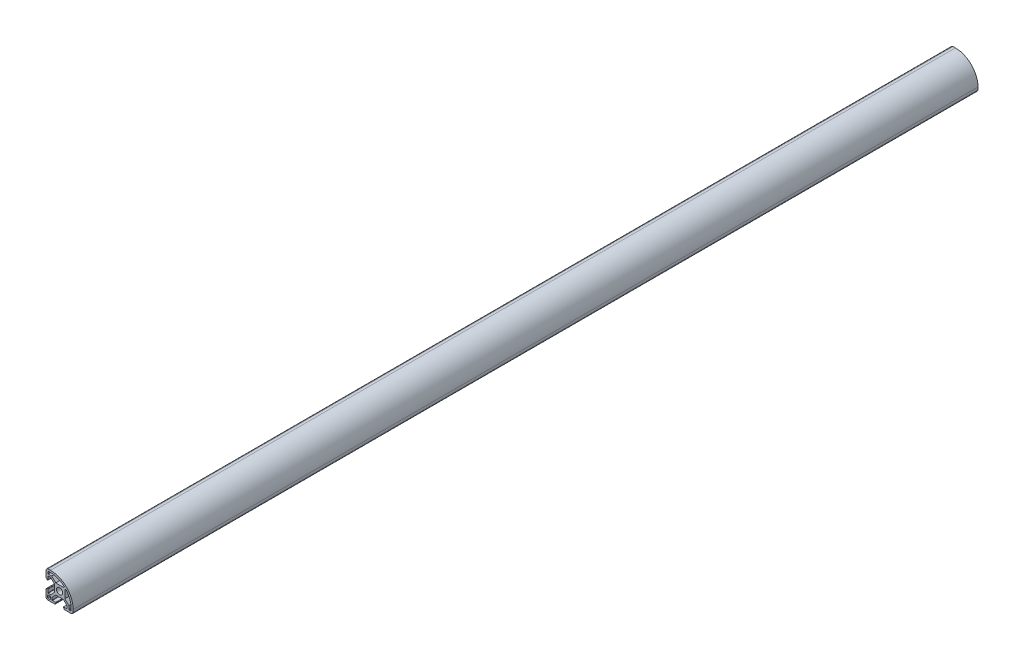
SolidWorks part; units mm, degrees
ref_plane "前视基准面" through (0, 0, 0) normal (0, 0, 1) x (1, 0, 0)
ref_plane "上视基准面" through (0, 0, 0) normal (0, 1, 0) x (1, 0, 0)
ref_plane "右视基准面" through (0, 0, 0) normal (1, 0, 0) x (0, 0, -1)
sketch "草图1" plane through (0, 0, 0) normal (0, 0, 1) x (1, 0, 0)
  line L0 (-29.9574, -7.0303) -> (-29.9574, -14.4303)
  line L1 (-9.632, 4.9507) -> (-10.7131, 3.8697)
  line L2 (-10.7131, 3.8697) -> (-19.2018, 3.8697)
  line L3 (-19.2018, 3.8697) -> (-23.6518, 8.3197)
  line L4 (-24.9574, 13.0697) -> (-27.4574, 13.0697)
  line L5 (-29.9574, 10.5697) -> (-29.9574, 3.1697)
  line L6 (-29.9574, 3.1697) -> (-29.1574, 3.1697)
  line L7 (-28.9574, 2.9697) -> (-28.9574, 2.1697)
  line L8 (-28.9574, 2.1697) -> (-28.0574, 2.1697)
  line L9 (-27.7574, 2.4697) -> (-27.7574, 6.0197)
  line L10 (-27.4574, 6.3197) -> (-24.7631, 6.3197)
  line L11 (-24.7631, 6.3197) -> (-20.7574, 2.314)
  line L12 (-20.7574, 2.314) -> (-20.7574, -6.1747)
  line L13 (-20.7574, -6.1747) -> (-24.7631, -10.1803)
  line L14 (-24.7631, -10.1803) -> (-27.4574, -10.1803)
  line L15 (-27.7574, -9.8803) -> (-27.7574, -6.3303)
  line L16 (-28.0574, -6.0303) -> (-28.9574, -6.0303)
  line L17 (-28.9574, -6.0303) -> (-28.9574, -6.8303)
  line L18 (-29.1574, -7.0303) -> (-29.9574, -7.0303)
  line L20 (-27.4574, -16.9303) -> (-20.0574, -16.9303)
  line L21 (-20.0574, -16.9303) -> (-20.0574, -16.1303)
  line L22 (-19.8574, -15.9303) -> (-19.0574, -15.9303)
  line L23 (-19.0574, -15.9303) -> (-19.0574, -15.0303)
  line L24 (-19.3574, -14.7303) -> (-22.9074, -14.7303)
  line L25 (-23.2074, -14.4303) -> (-23.2074, -11.736)
  line L26 (-23.2074, -11.736) -> (-19.2018, -7.7303)
  line L27 (-19.2018, -7.7303) -> (-10.7131, -7.7303)
  line L28 (-10.7131, -7.7303) -> (-6.7074, -11.736)
  line L29 (-6.7074, -11.736) -> (-6.7074, -14.4303)
  line L30 (-7.0074, -14.7303) -> (-10.5574, -14.7303)
  line L31 (-10.8574, -15.0303) -> (-10.8574, -15.9303)
  line L32 (-10.8574, -15.9303) -> (-10.0574, -15.9303)
  line L33 (-9.8574, -16.1303) -> (-9.8574, -16.9303)
  line L34 (-9.8574, -16.9303) -> (-2.4574, -16.9303)
  line L35 (0.0426, -14.4303) -> (0.0426, -11.9303)
  line L36 (-24.9574, 10.8697) -> (-27.4574, 10.8697)
  line L37 (-27.7574, 10.5697) -> (-27.7574, 8.6197)
  line L38 (-27.4574, 8.3197) -> (-23.6518, 8.3197)
  line L39 (-27.9324, -15.2053) -> (-25.2324, -15.2053)
  line L40 (-24.9324, -14.9053) -> (-24.9324, -12.2053)
  line L41 (-25.2324, -11.9053) -> (-27.9324, -11.9053)
  line L42 (-28.2324, -12.2053) -> (-28.2324, -14.9053)
  line L44 (-8.0764, 3.3951) -> (-9.1574, 2.314)
  line L45 (-9.1574, 2.314) -> (-9.1574, -6.1747)
  line L46 (-9.1574, -6.1747) -> (-4.7074, -10.6247)
  line L47 (-2.1574, -11.9303) -> (-2.1574, -14.4303)
  line L48 (-2.4574, -14.7303) -> (-4.4074, -14.7303)
  line L49 (-4.7074, -14.4303) -> (-4.7074, -10.6247)
  circle A0 centre (-14.9574, -1.9303) radius 3.4
  arc A1 (-27.4574, 13.0697) -> (-29.9574, 10.5697) centre (-27.4574, 10.5697) ccw
  arc A2 (-28.9574, 2.9697) -> (-29.1574, 3.1697) centre (-29.1574, 2.9697) ccw
  arc A3 (-28.0574, 2.1697) -> (-27.7574, 2.4697) centre (-28.0574, 2.4697) ccw
  arc A4 (-27.4574, 6.3197) -> (-27.7574, 6.0197) centre (-27.4574, 6.0197) ccw
  arc A5 (-27.7574, -9.8803) -> (-27.4574, -10.1803) centre (-27.4574, -9.8803) ccw
  arc A6 (-27.7574, -6.3303) -> (-28.0574, -6.0303) centre (-28.0574, -6.3303) ccw
  arc A7 (-29.1574, -7.0303) -> (-28.9574, -6.8303) centre (-29.1574, -6.8303) ccw
  arc A8 (-29.9574, -14.4303) -> (-27.4574, -16.9303) centre (-27.4574, -14.4303) ccw
  arc A9 (-19.8574, -15.9303) -> (-20.0574, -16.1303) centre (-19.8574, -16.1303) ccw
  arc A10 (-19.0574, -15.0303) -> (-19.3574, -14.7303) centre (-19.3574, -15.0303) ccw
  arc A11 (-23.2074, -14.4303) -> (-22.9074, -14.7303) centre (-22.9074, -14.4303) ccw
  arc A12 (-7.0074, -14.7303) -> (-6.7074, -14.4303) centre (-7.0074, -14.4303) ccw
  arc A13 (-10.5574, -14.7303) -> (-10.8574, -15.0303) centre (-10.5574, -15.0303) ccw
  arc A14 (-9.8574, -16.1303) -> (-10.0574, -15.9303) centre (-10.0574, -16.1303) ccw
  arc A15 (-2.4574, -16.9303) -> (0.0426, -14.4303) centre (-2.4574, -14.4303) ccw
  arc A16 (-27.4574, 10.8697) -> (-27.7574, 10.5697) centre (-27.4574, 10.5697) ccw
  arc A17 (-27.7574, 8.6197) -> (-27.4574, 8.3197) centre (-27.4574, 8.6197) ccw
  arc A18 (-25.2324, -15.2053) -> (-24.9324, -14.9053) centre (-25.2324, -14.9053) ccw
  arc A19 (-24.9324, -12.2053) -> (-25.2324, -11.9053) centre (-25.2324, -12.2053) ccw
  arc A20 (-27.9324, -11.9053) -> (-28.2324, -12.2053) centre (-27.9324, -12.2053) ccw
  arc A21 (-28.2324, -14.9053) -> (-27.9324, -15.2053) centre (-27.9324, -14.9053) ccw
  arc A22 (0.0426, -11.9303) -> (-24.9574, 13.0697) centre (-24.9574, -11.9303) ccw
  arc A23 (-9.632, 4.9507) -> (-24.9574, 10.8697) centre (-24.9574, -11.9303) ccw
  arc A24 (-2.4574, -14.7303) -> (-2.1574, -14.4303) centre (-2.4574, -14.4303) ccw
  arc A25 (-4.7074, -14.4303) -> (-4.4074, -14.7303) centre (-4.4074, -14.4303) ccw
  arc A26 (-2.1574, -11.9303) -> (-8.0764, 3.3951) centre (-24.9574, -11.9303) ccw
extrude "凸台-拉伸1" add sketch "草图1" along normal blind 1000
